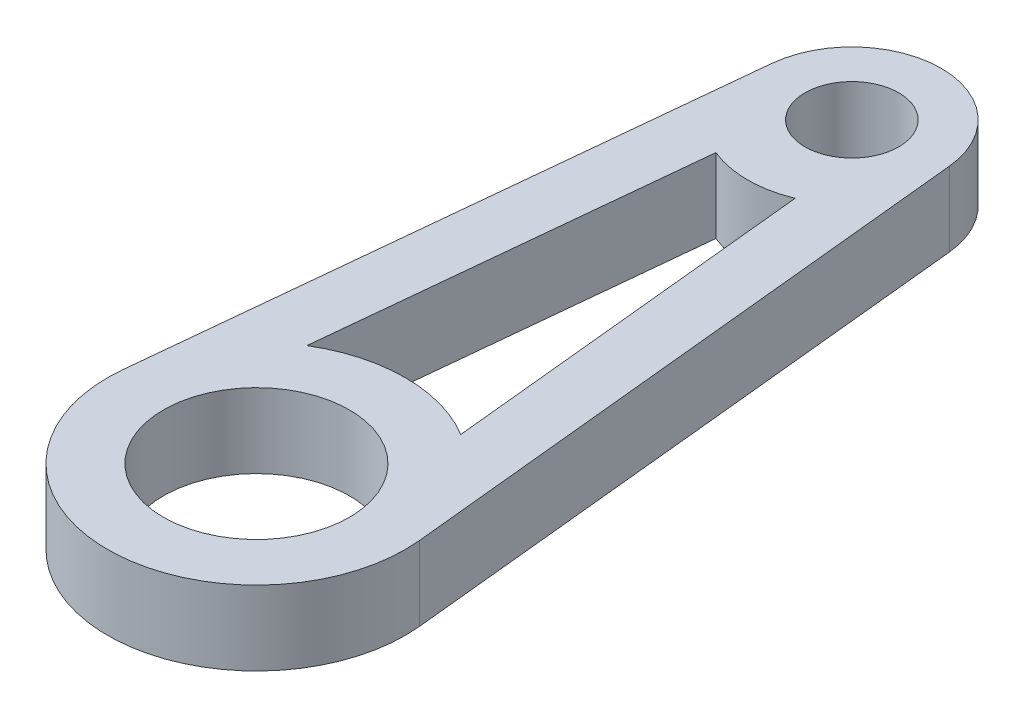
SolidWorks part; units mm, degrees
material "6061-T6 (SS)"
ref_plane "X-Y Datum" through (0, 0, 0) normal (0, 0, 1) x (1, 0, 0)
ref_plane "X-Z Datum" through (0, 0, 0) normal (0, 1, 0) x (1, 0, 0)
ref_plane "Y-Z Datum" through (0, 0, 0) normal (1, 0, 0) x (0, 0, -1)
sketch "Sketch1" plane through (0, 0, 0) normal (0, 1, 0) x (1, 0, 0)
  line L2 (-3.7909, 0.381) -> (-6.3182, -24.765)
  line L3 (3.7909, 0.381) -> (6.3182, -24.765)
  line L4 (3.2829, -19.9645) -> (1.6896, -4.1114)
  line L5 (-3.2829, -19.9645) -> (-1.6896, -4.1114)
  line L6 (0, -25.4) -> (0, 0) construction
  circle A0 centre (0, 0) radius 2
  circle A1 centre (0, -25.4) radius 3.9688
  arc A4 (3.7909, 0.381) -> (-3.7909, 0.381) centre (0, 0) ccw
  arc A5 (-6.3182, -24.765) -> (6.3182, -24.765) centre (0, -25.4) ccw
  arc A6 (1.6896, -4.1114) -> (-1.6896, -4.1114) centre (0, 0) cw
  arc A7 (3.2829, -19.9645) -> (-3.2829, -19.9645) centre (0, -25.4) ccw
  dimension "D1" = 4
  dimension "D2" = 7.9375
  dimension "D4" = 3.81
  dimension "D5" = 6.35
  dimension "D6" = 6.35
  dimension "D7" = 4.445
  dimension "D3" = 25.4
  dimension "D8" = 2.54
  dimension "D9" = 2.54
extrude "Boss-Extrude1" add sketch "Sketch1" against normal blind 3.175
